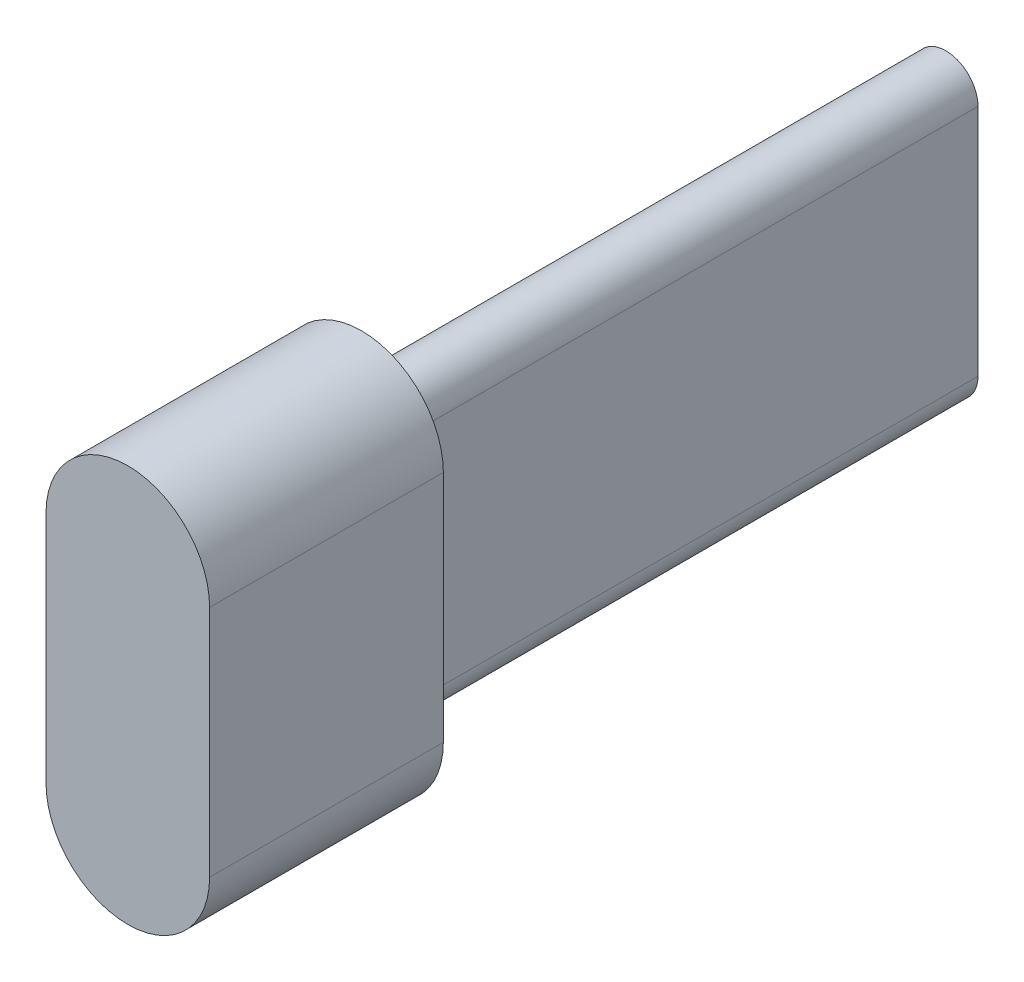
SolidWorks part; units mm, degrees
ref_plane "前视基准面" through (0, 0, 0) normal (0, 0, 1) x (1, 0, 0)
ref_plane "上视基准面" through (0, 0, 0) normal (0, 1, 0) x (1, 0, 0)
ref_plane "右视基准面" through (0, 0, 0) normal (1, 0, 0) x (0, 0, -1)
other "Configuration Table"
sketch "草图1" plane through (0, 0, 0) normal (0, 0, 1) x (1, 0, 0)
  line L0 (-4.3532, -34.1185) -> (-4.3532, -26.1185) construction
  line L1 (-6.3532, -26.1185) -> (-6.3532, -34.1185) construction
  line L6 (-3.8532, -34.1185) -> (-3.8532, -26.1185)
  line L7 (-6.8532, -26.1185) -> (-6.8532, -34.1185)
  line L8 (-3.8532, -34.1185) -> (-3.8532, -26.1185) construction
  line L9 (-6.8532, -26.1185) -> (-6.8532, -34.1185) construction
  line L12 (-6.4532, -26.1185) -> (-6.4532, -34.1185)
  line L13 (-4.2532, -34.1185) -> (-4.2532, -26.1185)
  arc A0 (-4.3532, -26.1185) -> (-6.3532, -26.1185) centre (-5.3532, -26.1185) ccw construction
  arc A1 (-6.3532, -34.1185) -> (-4.3532, -34.1185) centre (-5.3532, -34.1185) ccw construction
  arc A6 (-6.8532, -34.1185) -> (-3.8532, -34.1185) centre (-5.3532, -34.1185) ccw
  arc A7 (-3.8532, -26.1185) -> (-6.8532, -26.1185) centre (-5.3532, -26.1185) ccw
  arc A8 (-6.8532, -34.1185) -> (-3.8532, -34.1185) centre (-5.3532, -34.1185) ccw construction
  arc A9 (-3.8532, -26.1185) -> (-6.8532, -26.1185) centre (-5.3532, -26.1185) ccw construction
  arc A12 (-6.4532, -34.1185) -> (-4.2532, -34.1185) centre (-5.3532, -34.1185) ccw
  arc A13 (-4.2532, -26.1185) -> (-6.4532, -26.1185) centre (-5.3532, -26.1185) ccw
  dimension "D4" = 8
  dimension "D3" = 2
  dimension "D2" = 0
  dimension "D5" = 0.1
extrude "凸台-拉伸1" add sketch "草图1" against normal blind 20
sketch "草图2" plane through (0, 0, 0) normal (0, 0, 1) x (1, 0, 0)
  line L0 (-4.3532, -113.8815) -> (-4.3532, -105.8815) construction
  line L1 (-6.3532, -105.8815) -> (-6.3532, -113.8815) construction
  line L2 (-4.3532, -34.1185) -> (-4.3532, -26.1185) construction
  line L3 (-6.3532, -26.1185) -> (-6.3532, -34.1185) construction
  line L4 (-4.3532, -113.8815) -> (-4.3532, -105.8815) construction
  line L5 (-6.3532, -105.8815) -> (-6.3532, -113.8815) construction
  line L6 (-4.3532, -34.1185) -> (-4.3532, -26.1185) construction
  line L7 (-6.3532, -26.1185) -> (-6.3532, -34.1185) construction
  line L8 (-8.1532, -105.8815) -> (-8.1532, -113.8815)
  line L9 (-2.5532, -113.8815) -> (-2.5532, -105.8815)
  line L10 (-8.1532, -26.1185) -> (-8.1532, -34.1185)
  line L11 (-2.5532, -34.1185) -> (-2.5532, -26.1185)
  arc A0 (-6.3532, -113.8815) -> (-4.3532, -113.8815) centre (-5.3532, -113.8815) ccw construction
  arc A1 (-4.3532, -105.8815) -> (-6.3532, -105.8815) centre (-5.3532, -105.8815) ccw construction
  arc A2 (-6.3532, -34.1185) -> (-4.3532, -34.1185) centre (-5.3532, -34.1185) ccw construction
  arc A3 (-4.3532, -26.1185) -> (-6.3532, -26.1185) centre (-5.3532, -26.1185) ccw construction
  arc A4 (-6.3532, -113.8815) -> (-4.3532, -113.8815) centre (-5.3532, -113.8815) ccw construction
  arc A5 (-4.3532, -105.8815) -> (-6.3532, -105.8815) centre (-5.3532, -105.8815) ccw construction
  arc A6 (-6.3532, -34.1185) -> (-4.3532, -34.1185) centre (-5.3532, -34.1185) ccw construction
  arc A7 (-4.3532, -26.1185) -> (-6.3532, -26.1185) centre (-5.3532, -26.1185) ccw construction
  arc A8 (-8.1532, -113.8815) -> (-2.5532, -113.8815) centre (-5.3532, -113.8815) ccw
  arc A9 (-2.5532, -105.8815) -> (-8.1532, -105.8815) centre (-5.3532, -105.8815) ccw
  arc A10 (-8.1532, -34.1185) -> (-2.5532, -34.1185) centre (-5.3532, -34.1185) ccw
  arc A11 (-2.5532, -26.1185) -> (-8.1532, -26.1185) centre (-5.3532, -26.1185) ccw
extrude "凸台-拉伸2" add sketch "草图2" along normal blind 8 contours L11 A11 L10 A10
